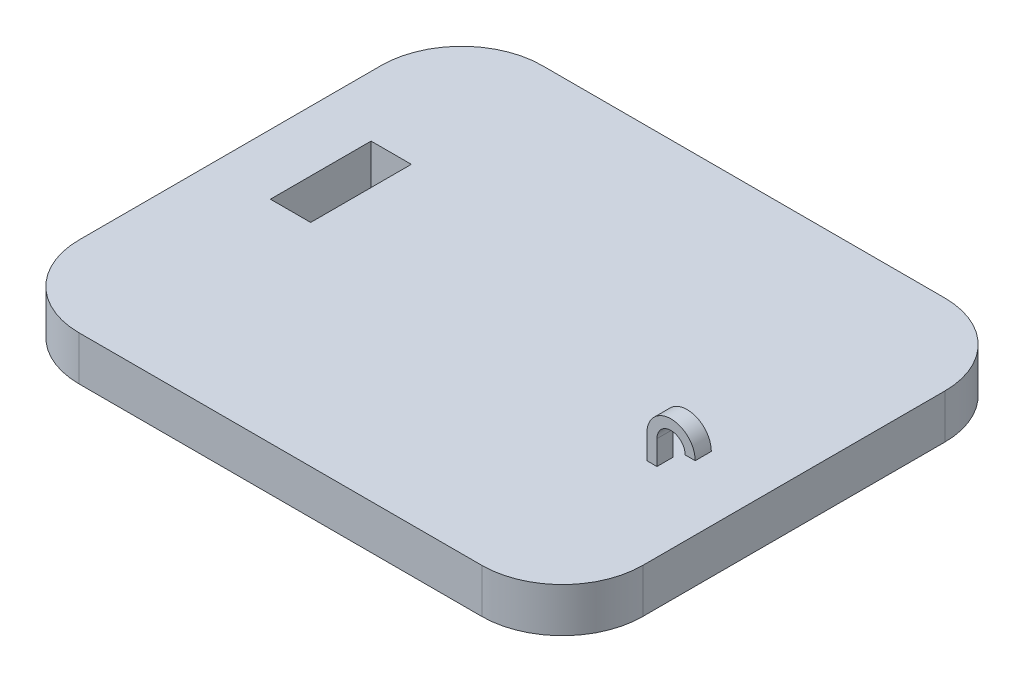
SolidWorks part; units mm, degrees
ref_plane "Front" through (0, 0, 0) normal (0, 0, 1) x (1, 0, 0)
ref_plane "Top" through (0, 0, 0) normal (0, 1, 0) x (1, 0, 0)
ref_plane "Right" through (0, 0, 0) normal (1, 0, 0) x (0, 0, -1)
sketch "Sketch2" plane through (0, 0, 0) normal (0, 1, 0) x (1, 0, 0)
  line L1 (-80, 50) -> (60, 50)
  line L2 (-80, 50) -> (-80, -65)
  line L3 (-80, -65) -> (60, -65)
  line L4 (60, 50) -> (60, -65)
  dimension "D1" = 140
  dimension "D2" = 115
  dimension "D3" = 65
  dimension "D4" = 80
extrude "Boss-Extrude1" add sketch "Sketch2" against normal blind 11 contours L3 L4 L1 L2
sketch "Sketch3" plane through (0, 0, 0) normal (0, 1, 0) x (1, 0, 0)
  line L1 (-65, 12.5) -> (-55, 12.5)
  line L2 (-65, 12.5) -> (-65, -12.5)
  line L3 (-65, -12.5) -> (-55, -12.5)
  line L4 (-55, 12.5) -> (-55, -12.5)
  line L5 (-51, -17.5) -> (-66, -17.5) construction
  line L7 (-70, 29.5) -> (-70, -29.5) construction
  dimension "D1" = 25
  dimension "D2" = 10
  dimension "D3" = 5
  dimension "D4" = 5
extrude "Cut-Extrude1" cut sketch "Sketch3" against normal through all
fillet "Fillet1" radius 20 4 edges at (60, -5.5, -50) (-80, -5.5, -50) (-80, -5.5, 65) (60, -5.5, 65)
ref_plane "Plane1" through (0, 0, 20) normal (0, 0, 1) x (1, 0, 0)
sketch "Sketch4" plane through (0, 0, 20) normal (0, 0, 1) x (1, 0, 0)
  line L6 (38, 6) -> (38, 0)
  line L8 (-60, 0) -> (40, 0) construction
  line L9 (40.5, 6) -> (40.5, 0)
  line L10 (60, 0) -> (40, 0) construction
  line L11 (47.5, 6) -> (50, 6)
  line L12 (38, 0) -> (40.5, 0)
  arc A0 (47.5, 6) -> (40.5, 6) centre (44, 6) ccw
  arc A1 (50, 6) -> (38, 6) centre (44, 6) ccw
extrude "Boss-Extrude2" add sketch "Sketch4" along normal mid plane 4
